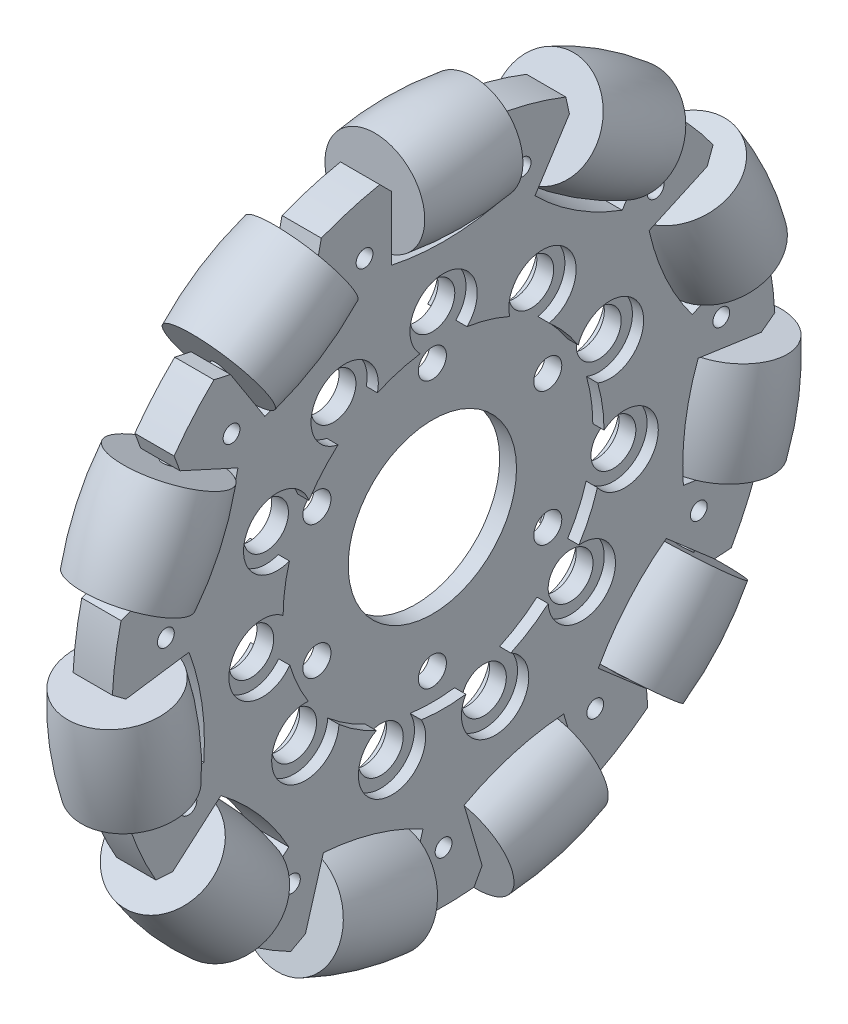
SolidWorks part; units mm, degrees
ref_plane "Front Plane" through (0, 0, 0) normal (0, 0, 1) x (1, 0, 0)
ref_plane "Top Plane" through (0, 0, 0) normal (0, 1, 0) x (1, 0, 0)
ref_plane "Right Plane" through (0, 0, 0) normal (1, 0, 0) x (0, 0, -1)
sketch "Sketch1" plane through (0, 0, 0) normal (1, 0, 0) x (0, 0, -1)
  line L0 (0, 0) -> (0, 23.75) construction
  line L1 (0, 0) -> (0, 32.6) construction
  line L2 (-9.25, 55.8716) -> (-9.25, 44.5)
  line L3 (9.25, 55.8716) -> (9.25, 44.5)
  line L5 (-9.25, 55.8716) -> (-11.3736, 57.9953)
  line L6 (9.25, 55.8716) -> (11.3736, 57.9953)
  line L7 (22.4249, 52.0031) -> (21.7865, 54.9378)
  line L8 (22.4249, 52.0031) -> (16.2769, 42.4367)
  line L10 (37.9881, 42.0013) -> (31.8401, 32.4349)
  line L11 (37.9881, 42.0013) -> (40.9227, 42.6397)
  line L12 (46.98, 31.624) -> (48.0296, 34.4379)
  line L13 (46.98, 31.624) -> (36.636, 26.9001)
  line L15 (54.6652, 14.7958) -> (44.3212, 10.0719)
  line L16 (54.6652, 14.7958) -> (57.4791, 13.7463)
  line L17 (56.6194, 1.2045) -> (59.0236, 3.0043)
  line L18 (56.6194, 1.2045) -> (45.3635, 2.8228)
  line L20 (53.9865, -17.1072) -> (42.7306, -15.4889)
  line L21 (53.9865, -17.1072) -> (55.7863, -19.5114)
  line L22 (48.2824, -29.5975) -> (51.278, -29.3832)
  line L23 (48.2824, -29.5975) -> (39.6883, -22.1506)
  line L25 (36.1675, -43.5788) -> (27.5734, -36.132)
  line L26 (36.1675, -43.5788) -> (36.3818, -46.5744)
  line L27 (24.6162, -51.0024) -> (27.2521, -52.4417)
  line L28 (24.6162, -51.0024) -> (21.4124, -40.0914)
  line L30 (6.8655, -56.2145) -> (3.6618, -45.3035)
  line L31 (6.8655, -56.2145) -> (5.4262, -58.8504)
  line L32 (-6.8655, -56.2145) -> (-5.4262, -58.8504)
  line L33 (-6.8655, -56.2145) -> (-3.6618, -45.3035)
  line L35 (-24.6162, -51.0024) -> (-21.4124, -40.0914)
  line L36 (-24.6162, -51.0024) -> (-27.2521, -52.4417)
  line L37 (-36.1675, -43.5788) -> (-36.3818, -46.5744)
  line L38 (-36.1675, -43.5788) -> (-27.5734, -36.132)
  line L40 (-48.2824, -29.5975) -> (-39.6883, -22.1506)
  line L41 (-48.2824, -29.5975) -> (-51.278, -29.3832)
  line L42 (-53.9865, -17.1072) -> (-55.7863, -19.5114)
  line L43 (-53.9865, -17.1072) -> (-42.7306, -15.4889)
  line L45 (-56.6194, 1.2045) -> (-45.3635, 2.8228)
  line L46 (-56.6194, 1.2045) -> (-59.0236, 3.0043)
  line L47 (-54.6652, 14.7958) -> (-57.4791, 13.7463)
  line L48 (-54.6652, 14.7958) -> (-44.3212, 10.0719)
  line L50 (-46.98, 31.624) -> (-36.636, 26.9001)
  line L51 (-46.98, 31.624) -> (-48.0296, 34.4379)
  line L52 (-37.9881, 42.0013) -> (-40.9227, 42.6397)
  line L53 (-37.9881, 42.0013) -> (-31.8401, 32.4349)
  line L55 (-22.4249, 52.0031) -> (-16.2769, 42.4367)
  line L56 (-22.4249, 52.0031) -> (-21.7865, 54.9378)
  line L57 (-14.0866, 47.9746) -> (0, 0) construction
  circle A0 centre (0, 0) radius 15
  arc A1 (-11.3736, 57.9953) -> (-21.7865, 54.9378) centre (0, 0) ccw
  circle A2 centre (0, 23.75) radius 2.5
  circle A3 centre (0, 32.6) radius 4
  circle A4 centre (0, 0) radius 28.6 construction
  circle A5 centre (17.6249, 27.4249) radius 4
  circle A6 centre (29.654, 13.5425) radius 4
  circle A7 centre (32.2682, -4.6395) radius 4
  circle A8 centre (24.6374, -21.3485) radius 4
  circle A9 centre (9.1845, -31.2795) radius 4
  circle A10 centre (-9.1845, -31.2795) radius 4
  circle A11 centre (-24.6374, -21.3485) radius 4
  circle A12 centre (-32.2682, -4.6395) radius 4
  circle A13 centre (-29.654, 13.5425) radius 4
  circle A14 centre (-17.6249, 27.4249) radius 4
  circle A15 centre (20.5681, 11.875) radius 2.5
  circle A16 centre (20.5681, -11.875) radius 2.5
  circle A17 centre (0, -23.75) radius 2.5
  circle A18 centre (-20.5681, -11.875) radius 2.5
  circle A19 centre (-20.5681, 11.875) radius 2.5
  circle A20 centre (0, 0) radius 63.5 construction
  arc A21 (21.7865, 54.9378) -> (11.3736, 57.9953) centre (0, 0) ccw
  arc A22 (-40.9227, 42.6397) -> (-48.0296, 34.4379) centre (0, 0) ccw
  arc A23 (59.0236, 3.0043) -> (40.9227, 42.6397) centre (0, 0) ccw
  arc A24 (51.278, -29.3832) -> (55.7863, -19.5114) centre (0, 0) ccw
  arc A25 (27.2521, -52.4417) -> (36.3818, -46.5744) centre (0, 0) ccw
  arc A26 (-5.4262, -58.8504) -> (5.4262, -58.8504) centre (0, 0) ccw
  arc A27 (-36.3818, -46.5744) -> (-27.2521, -52.4417) centre (0, 0) ccw
  arc A28 (-55.7863, -19.5114) -> (-51.278, -29.3832) centre (0, 0) ccw
  arc A29 (-57.4791, 13.7463) -> (-59.0236, 3.0043) centre (0, 0) ccw
  circle A30 centre (-14.0866, 47.9746) radius 1.5
  circle A31 centre (14.0866, 47.9746) radius 1.5
  circle A32 centre (37.7875, 32.743) radius 1.5
  circle A33 centre (49.4911, 7.1157) radius 1.5
  circle A34 centre (45.4816, -20.7708) radius 1.5
  circle A35 centre (27.032, -42.0627) radius 1.5
  circle A36 centre (0, -50) radius 1.5
  circle A37 centre (-27.032, -42.0627) radius 1.5
  circle A38 centre (-45.4816, -20.7708) radius 1.5
  circle A39 centre (-49.4911, 7.1157) radius 1.5
  circle A40 centre (-37.7875, 32.743) radius 1.5
  arc A41 (-9.25, 44.5) -> (9.25, 44.5) centre (0, 87.2798) ccw
  arc A42 (16.2769, 42.4367) -> (31.8401, 32.4349) centre (47.187, 73.4245) ccw
  arc A43 (36.636, 26.9001) -> (44.3212, 10.0719) centre (79.3925, 36.2573) ccw
  arc A44 (45.3635, 2.8228) -> (42.7306, -15.4889) centre (86.3914, -12.4212) ccw
  arc A45 (39.6883, -22.1506) -> (27.5734, -36.132) centre (65.9617, -57.1561) ccw
  arc A46 (21.4124, -40.0914) -> (3.6618, -45.3035) centre (24.5896, -83.7444) ccw
  arc A47 (-3.6618, -45.3035) -> (-21.4124, -40.0914) centre (-24.5896, -83.7444) ccw
  arc A48 (-27.5734, -36.132) -> (-39.6883, -22.1506) centre (-65.9617, -57.1561) ccw
  arc A49 (-42.7306, -15.4889) -> (-45.3635, 2.8228) centre (-86.3914, -12.4212) ccw
  arc A50 (-44.3212, 10.0719) -> (-36.636, 26.9001) centre (-79.3925, 36.2573) ccw
  arc A51 (-31.8401, 32.4349) -> (-16.2769, 42.4367) centre (-47.187, 73.4245) ccw
  point P31 (0, 0)
  point P42 (0, 0)
  point P46 (0, 63.5)
  point P50 (0, 43.5)
  point P112 (0, 0)
  point P135 (0, 0)
  point P166 (0, 0)
  dimension "D1" = 118.2
  dimension "D2" = 30
  dimension "D3" = 5
  dimension "D4" = 8
  dimension "D6" = 57.2
  dimension "D10" = 127
  dimension "D15" = 3
  dimension "D5" = 23.75
  dimension "D9" = 9.25
  dimension "D11" = 20
  dimension "D12" = 11
  dimension "D13" = 16.364
  dimension "D14" = 50
  dimension "D17" = 11
  dimension "D7" = 11
  dimension "D8" = 6
  dimension "D16" = 11
extrude "Boss-Extrude1" add sketch "Sketch1" along normal blind 3
sketch "Sketch3" plane through (0, 0, 0) normal (-1, 0, 0) x (0, 0, 1)
  line L0 (9.25, 55.8716) -> (9.25, 44.5) construction
  line L1 (9.25, 55.8716) -> (11.3736, 57.9953) construction
  line L2 (-9.25, 55.8716) -> (-11.3736, 57.9953) construction
  line L4 (-9.25, 55.8716) -> (-9.25, 44.5) construction
  line L5 (9.25, 55.8716) -> (9.25, 44.5)
  line L6 (9.25, 55.8716) -> (11.3736, 57.9953)
  line L7 (-9.25, 55.8716) -> (-11.3736, 57.9953)
  line L9 (-9.25, 55.8716) -> (-9.25, 44.5)
  line L10 (37.9881, 42.0013) -> (31.8401, 32.4349)
  line L11 (37.9881, 42.0013) -> (40.9227, 42.6397)
  line L12 (22.4249, 52.0031) -> (21.7865, 54.9378)
  line L14 (22.4249, 52.0031) -> (16.2769, 42.4367)
  line L15 (54.6652, 14.7958) -> (44.3212, 10.0719)
  line L16 (54.6652, 14.7958) -> (57.4791, 13.7463)
  line L17 (46.98, 31.624) -> (48.0296, 34.4379)
  line L19 (46.98, 31.624) -> (36.636, 26.9001)
  line L20 (53.9865, -17.1072) -> (42.7306, -15.4889)
  line L21 (53.9865, -17.1072) -> (55.7863, -19.5114)
  line L22 (56.6194, 1.2045) -> (59.0236, 3.0043)
  line L24 (56.6194, 1.2045) -> (45.3635, 2.8228)
  line L25 (36.1675, -43.5788) -> (27.5734, -36.132)
  line L26 (36.1675, -43.5788) -> (36.3818, -46.5744)
  line L27 (48.2824, -29.5975) -> (51.278, -29.3832)
  line L29 (48.2824, -29.5975) -> (39.6883, -22.1506)
  line L30 (6.8655, -56.2145) -> (3.6618, -45.3035)
  line L31 (6.8655, -56.2145) -> (5.4262, -58.8504)
  line L32 (24.6162, -51.0024) -> (27.2521, -52.4417)
  line L34 (24.6162, -51.0024) -> (21.4124, -40.0914)
  line L35 (-24.6162, -51.0024) -> (-21.4124, -40.0914)
  line L36 (-24.6162, -51.0024) -> (-27.2521, -52.4417)
  line L37 (-6.8655, -56.2145) -> (-5.4262, -58.8504)
  line L39 (-6.8655, -56.2145) -> (-3.6618, -45.3035)
  line L40 (-48.2824, -29.5975) -> (-39.6883, -22.1506)
  line L41 (-48.2824, -29.5975) -> (-51.278, -29.3832)
  line L42 (-36.1675, -43.5788) -> (-36.3818, -46.5744)
  line L44 (-36.1675, -43.5788) -> (-27.5734, -36.132)
  line L45 (-56.6194, 1.2045) -> (-45.3635, 2.8228)
  line L46 (-56.6194, 1.2045) -> (-59.0236, 3.0043)
  line L47 (-53.9865, -17.1072) -> (-55.7863, -19.5114)
  line L49 (-53.9865, -17.1072) -> (-42.7306, -15.4889)
  line L50 (-46.98, 31.624) -> (-36.636, 26.9001)
  line L51 (-46.98, 31.624) -> (-48.0296, 34.4379)
  line L52 (-54.6652, 14.7958) -> (-57.4791, 13.7463)
  line L54 (-54.6652, 14.7958) -> (-44.3212, 10.0719)
  line L55 (-22.4249, 52.0031) -> (-16.2769, 42.4367)
  line L56 (-22.4249, 52.0031) -> (-21.7865, 54.9378)
  line L57 (-37.9881, 42.0013) -> (-40.9227, 42.6397)
  line L59 (-37.9881, 42.0013) -> (-31.8401, 32.4349)
  arc A0 (-11.3736, 57.9953) -> (-21.7865, 54.9378) centre (0, 0) ccw
  arc A1 (-18.8109, 21.5432) -> (-24.001, 15.5535) centre (0, 0) ccw
  circle A2 centre (-14.0866, 47.9746) radius 1.5 construction
  circle A3 centre (-14.0866, 47.9746) radius 1.5
  circle A4 centre (14.0866, 47.9746) radius 1.5
  circle A5 centre (37.7875, 32.743) radius 1.5
  circle A6 centre (49.4911, 7.1157) radius 1.5
  circle A7 centre (45.4816, -20.7708) radius 1.5
  circle A8 centre (27.032, -42.0627) radius 1.5
  circle A9 centre (0, -50) radius 1.5
  circle A10 centre (-27.032, -42.0627) radius 1.5
  circle A11 centre (-45.4816, -20.7708) radius 1.5
  circle A12 centre (-49.4911, 7.1157) radius 1.5
  circle A13 centre (-37.7875, 32.743) radius 1.5
  arc A14 (4.1775, 28.2933) -> (-4.1775, 28.2933) centre (0, 32.6) ccw
  arc A15 (18.8109, 21.5432) -> (11.7821, 26.0604) centre (17.6249, 27.4249) ccw
  arc A16 (27.4719, 7.9534) -> (24.001, 15.5535) centre (29.654, 13.5425) ccw
  arc A17 (27.4107, -8.1616) -> (28.5998, 0.1085) centre (32.2682, -4.6395) ccw
  arc A18 (18.6469, -21.6853) -> (24.1183, -15.371) centre (24.6374, -21.3485) ccw
  arc A19 (3.9628, -28.3241) -> (11.9795, -25.9702) centre (9.1845, -31.2795) ccw
  arc A20 (-11.9795, -25.9702) -> (-3.9628, -28.3241) centre (-9.1845, -31.2795) ccw
  arc A21 (-24.1183, -15.371) -> (-18.6469, -21.6853) centre (-24.6374, -21.3485) ccw
  arc A22 (-28.5998, 0.1085) -> (-27.4107, -8.1616) centre (-32.2682, -4.6395) ccw
  arc A23 (-24.001, 15.5535) -> (-27.4719, 7.9534) centre (-29.654, 13.5425) ccw
  arc A24 (-11.7821, 26.0604) -> (-18.8109, 21.5432) centre (-17.6249, 27.4249) ccw
  arc A25 (21.7865, 54.9378) -> (11.3736, 57.9953) centre (0, 0) ccw
  arc A26 (-4.1775, 28.2933) -> (-11.7821, 26.0604) centre (0, 0) ccw
  arc A27 (11.7821, 26.0604) -> (4.1775, 28.2933) centre (0, 0) ccw
  arc A28 (-27.4719, 7.9534) -> (-28.5998, 0.1085) centre (0, 0) ccw
  arc A29 (-27.4107, -8.1616) -> (-24.1183, -15.371) centre (0, 0) ccw
  arc A30 (-40.9227, 42.6397) -> (-48.0296, 34.4379) centre (0, 0) ccw
  arc A31 (-57.4791, 13.7463) -> (-59.0236, 3.0043) centre (0, 0) ccw
  arc A32 (-55.7863, -19.5114) -> (-51.278, -29.3832) centre (0, 0) ccw
  arc A33 (-18.6469, -21.6853) -> (-11.9795, -25.9702) centre (0, 0) ccw
  arc A34 (-36.3818, -46.5744) -> (-27.2521, -52.4417) centre (0, 0) ccw
  arc A35 (-3.9628, -28.3241) -> (3.9628, -28.3241) centre (0, 0) ccw
  arc A36 (-5.4262, -58.8504) -> (5.4262, -58.8504) centre (0, 0) ccw
  arc A37 (11.9795, -25.9702) -> (18.6469, -21.6853) centre (0, 0) ccw
  arc A38 (27.2521, -52.4417) -> (36.3818, -46.5744) centre (0, 0) ccw
  arc A39 (51.278, -29.3832) -> (55.7863, -19.5114) centre (0, 0) ccw
  arc A40 (24.1183, -15.371) -> (27.4107, -8.1616) centre (0, 0) ccw
  arc A41 (28.5998, 0.1085) -> (27.4719, 7.9534) centre (0, 0) ccw
  arc A42 (59.0236, 3.0043) -> (57.4791, 13.7463) centre (0, 0) ccw
  arc A43 (24.001, 15.5535) -> (18.8109, 21.5432) centre (0, 0) ccw
  arc A44 (48.0296, 34.4379) -> (40.9227, 42.6397) centre (0, 0) ccw
  arc A45 (-9.25, 44.5) -> (9.25, 44.5) centre (0, 87.2798) ccw construction
  arc A46 (-9.25, 44.5) -> (9.25, 44.5) centre (0, 87.2798) ccw
  arc A47 (16.2769, 42.4367) -> (31.8401, 32.4349) centre (47.187, 73.4245) ccw
  arc A48 (36.636, 26.9001) -> (44.3212, 10.0719) centre (79.3925, 36.2573) ccw
  arc A49 (45.3635, 2.8228) -> (42.7306, -15.4889) centre (86.3914, -12.4212) ccw
  arc A50 (39.6883, -22.1506) -> (27.5734, -36.132) centre (65.9617, -57.1561) ccw
  arc A51 (21.4124, -40.0914) -> (3.6618, -45.3035) centre (24.5896, -83.7444) ccw
  arc A52 (-3.6618, -45.3035) -> (-21.4124, -40.0914) centre (-24.5896, -83.7444) ccw
  arc A53 (-27.5734, -36.132) -> (-39.6883, -22.1506) centre (-65.9617, -57.1561) ccw
  arc A54 (-42.7306, -15.4889) -> (-45.3635, 2.8228) centre (-86.3914, -12.4212) ccw
  arc A55 (-44.3212, 10.0719) -> (-36.636, 26.9001) centre (-79.3925, 36.2573) ccw
  arc A56 (-31.8401, 32.4349) -> (-16.2769, 42.4367) centre (-47.187, 73.4245) ccw
  point P95 (0, 0)
  point P119 (0, 0)
  point P161 (0, 0)
  dimension "D2" = 12
  dimension "D1" = 11
  dimension "D3" = 11
  dimension "D4" = 11
extrude "Boss-Extrude2" add sketch "Sketch3" along normal blind 2
pattern_linear "LPattern1" count 2 spacing 5 along (1, 0, 0) of "Boss-Extrude2"
ref_plane "Plane1" through (1.5, 0, 0) normal (1, 0, 0) x (0, 0, -1)
sketch "Sketch5" plane through (1.5, 0, 0) normal (1, 0, 0) x (0, 0, -1)
  line L1 (0, 63.5) -> (0, 44.5) construction
  line L2 (9.25, 54) -> (-9.25, 54) construction
  line L5 (-9.25, 55.25) -> (-9.25, 54)
  line L6 (9.25, 55.25) -> (8.75, 55.25)
  line L10 (-9.25, 55.8716) -> (-9.25, 44.5) construction
  line L11 (-8.75, 55.25) -> (-8.75, 62.8943)
  line L12 (-8.75, 55.25) -> (-9.25, 55.25)
  line L14 (8.75, 55.25) -> (8.75, 62.8943)
  line L15 (9.25, 55.25) -> (9.25, 54)
  line L17 (-9.25, 54) -> (9.25, 54)
  arc A0 (8.75, 62.8943) -> (-8.75, 62.8943) centre (0, 0) ccw
  point P5 (0, 63.5)
  point P6 (0, 44.5)
  point P12 (0, 54)
  point P13 (-9.25, 54)
  point P15 (0, 54)
  dimension "D2" = 127
  dimension "D1" = 19
revolve "Revolve1" add sketch "Sketch5" angle 360 about L17
pattern_circular "CirPattern1" count 11 over 360 about axis through (0, 0, 0) along (1, 0, 0) of "Revolve1"
